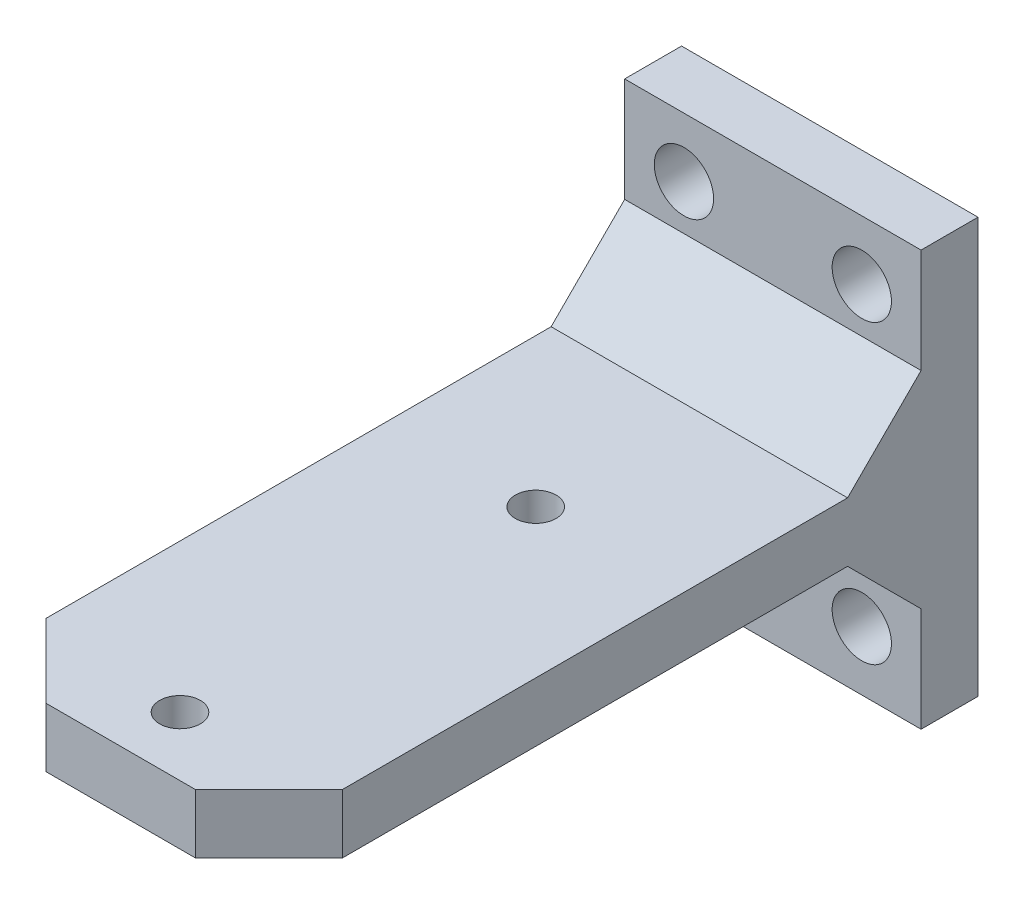
SolidWorks part; units mm, degrees
material "1060 Alloy"
ref_plane "Front Plane" through (0, 0, 0) normal (0, 0, 1) x (1, 0, 0)
ref_plane "Top Plane" through (0, 0, 0) normal (0, 1, 0) x (1, 0, 0)
ref_plane "Right Plane" through (0, 0, 0) normal (1, 0, 0) x (0, 0, -1)
sketch "Sketch1" plane through (0, 0, 0) normal (1, 0, 0) x (0, 0, -1)
  line L0 (0, 0) -> (0, 44.45)
  line L1 (0, 44.45) -> (-6.35, 44.45)
  line L2 (-6.35, 44.45) -> (-6.35, 25.4)
  line L3 (-6.35, 25.4) -> (-76.2, 25.4)
  line L4 (-76.2, 25.4) -> (-76.2, 19.05)
  line L5 (-76.2, 19.05) -> (-6.35, 19.05)
  line L6 (-6.35, 19.05) -> (-6.35, 0)
  line L7 (-6.35, 0) -> (0, 0)
  point P8 (-76.2, 22.225)
  point P10 (0, 22.225)
  dimension "D1" = 44.45
  dimension "D2" = 6.35
  dimension "D3" = 6.35
  dimension "D4" = 76.2
  dimension "D5" = 6.35
extrude "Boss-Extrude1" add sketch "Sketch1" along normal blind 31.75
sketch "Sketch2" plane through (0, 0, 6.35) normal (0, 0, 1) x (1, 0, 0)
  line L0 (6.35, 38.1) -> (6.35, 6.35) construction
  line L1 (6.35, 6.35) -> (25.4, 6.35) construction
  line L2 (25.4, 6.35) -> (25.4, 38.1) construction
  line L3 (25.4, 38.1) -> (6.35, 38.1) construction
  line L4 (6.35, 38.1) -> (25.4, 6.35) construction
  line L5 (25.4, 38.1) -> (6.35, 6.35) construction
  line L6 (0, 44.45) -> (31.75, 0) construction
  line L7 (31.75, 44.45) -> (0, 0) construction
  circle A0 centre (6.35, 38.1) radius 3.175
  circle A1 centre (25.4, 38.1) radius 3.175
  circle A2 centre (6.35, 6.35) radius 3.175
  circle A3 centre (25.4, 6.35) radius 3.175
  point P16 (15.875, 22.225)
  point P17 (15.875, 22.225)
  dimension "D3" = 6.35
  dimension "D1" = 31.75
  dimension "D2" = 19.05
extrude "Cut-Extrude1" cut sketch "Sketch2" against normal blind 19.05
chamfer "Chamfer1" distance 7.874 angle 45 2 edges at (15.875, 19.05, 6.35) (15.875, 25.4, 6.35)
sketch "Sketch3" plane through (0, 25.4, 0) normal (0, 1, 0) x (1, 0, 0)
  line L0 (15.875, -31.75) -> (15.875, -69.85) construction
  line L2 (0, -14.224) -> (0, -76.2) construction
  line L3 (31.75, -76.2) -> (0, -76.2) construction
  circle A0 centre (15.875, -69.85) radius 2.1828
  circle A1 centre (15.875, -31.75) radius 2.1828
  dimension "D1" = 4.3656
  dimension "D2" = 4.3656
  dimension "D3" = 38.1
  dimension "D4" = 15.875
  dimension "D5" = 6.35
extrude "Cut-Extrude2" cut sketch "Sketch3" against normal blind 19.05 contours A1 | A0
chamfer "Chamfer2" distance 7.874 angle 45 2 edges at (31.75, 22.225, 76.2) (0, 22.225, 76.2)
chamfer "Chamfer3" distance 0.254 angle 45 8 edges at (15.875, 0, 0) (31.75, 22.225, 0) (15.875, 44.45, 0) (0, 22.225, 0) (9.525, 38.1, 0) (28.575, 6.35, 0) (9.525, 6.35, 0) (28.575, 38.1, 0)
